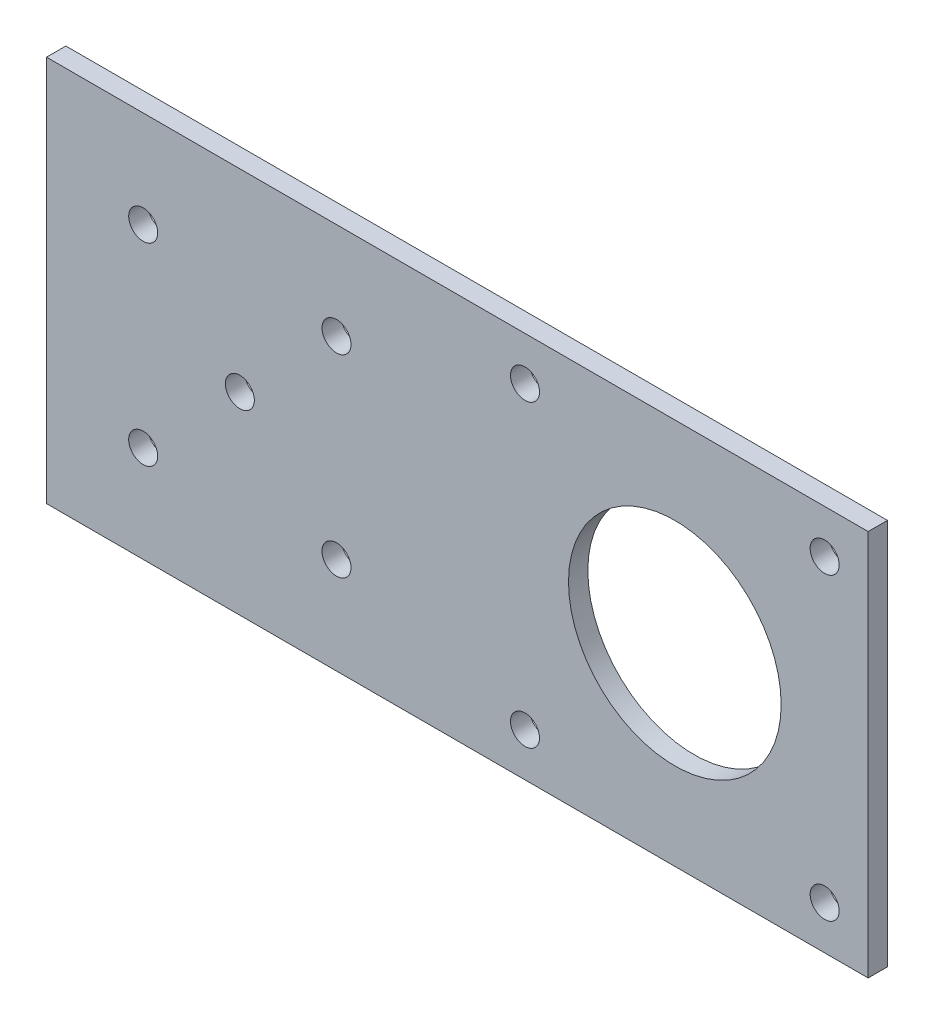
SolidWorks part; units mm, degrees
ref_plane "Front Plane" through (0, 0, 0) normal (0, 0, 1) x (1, 0, 0)
ref_plane "Top Plane" through (0, 0, 0) normal (0, 1, 0) x (1, 0, 0)
ref_plane "Right Plane" through (0, 0, 0) normal (1, 0, 0) x (0, 0, -1)
sketch "Sketch1" plane through (0, 0, 0) normal (0, 0, 1) x (1, 0, 0)
  line L1 (-42.5, 20) -> (42.5, 20)
  line L2 (-42.5, 20) -> (-42.5, -20)
  line L3 (-42.5, -20) -> (42.5, -20)
  line L4 (42.5, 20) -> (42.5, -20)
  line L5 (-42.5, 20) -> (42.5, -20) construction
  line L6 (-42.5, -20) -> (42.5, 20) construction
  point P0 (0, 0)
  dimension "D1" = 85
  dimension "D2" = 40
extrude "Boss-Extrude1" add sketch "Sketch1" along normal mid plane 2
sketch "Sketch2" plane through (0, 0, 1) normal (0, 0, 1) x (1, 0, 0)
  line L0 (1.1, 0) -> (-1.1, 0) construction
  line L1 (42.5, -20) -> (42.5, 20) construction
  line L2 (-32.5, 10) -> (-12.5, 10) construction
  line L3 (42.5, 20) -> (-42.5, 20) construction
  line L4 (-42.5, 20) -> (-42.5, -20) construction
  line L5 (-42.5, -20) -> (42.5, -20) construction
  circle A0 centre (22.5, 0) radius 11
  circle A1 centre (-22.5, 0) radius 1.5
  circle A2 centre (-32.5, 10) radius 1.5
  circle A3 centre (-12.5, 10) radius 1.5
  circle A4 centre (-12.5, -10) radius 1.5
  circle A5 centre (-32.5, -10) radius 1.5
  dimension "D1" = 22
  dimension "D3" = 3
  dimension "D2" = 20
  dimension "D6" = 20
  dimension "D7" = 10
  dimension "D8" = 10
  dimension "D9" = 20
  dimension "D10" = 10
  dimension "D4" = 2
  dimension "D5" = 2
extrude "Cut-Extrude1" cut sketch "Sketch2" against normal blind 2
sketch "Sketch3" plane through (0, 0, 1) normal (0, 0, 1) x (1, 0, 0)
  line L0 (42.5, 20) -> (-42.5, 20) construction
  line L1 (42.5, -20) -> (42.5, 20) construction
  circle A0 centre (7, 15.5) radius 1.5
  circle A1 centre (38, 15.5) radius 1.5
  circle A2 centre (38, -15.5) radius 1.5
  circle A3 centre (7, -15.5) radius 1.5
  dimension "D1" = 3
  dimension "D4" = 4.5
  dimension "D5" = 4.5
  dimension "D6" = 31
  dimension "D7" = 31
  dimension "D2" = 2
  dimension "D3" = 2
extrude "Cut-Extrude2" cut sketch "Sketch3" against normal blind 10
